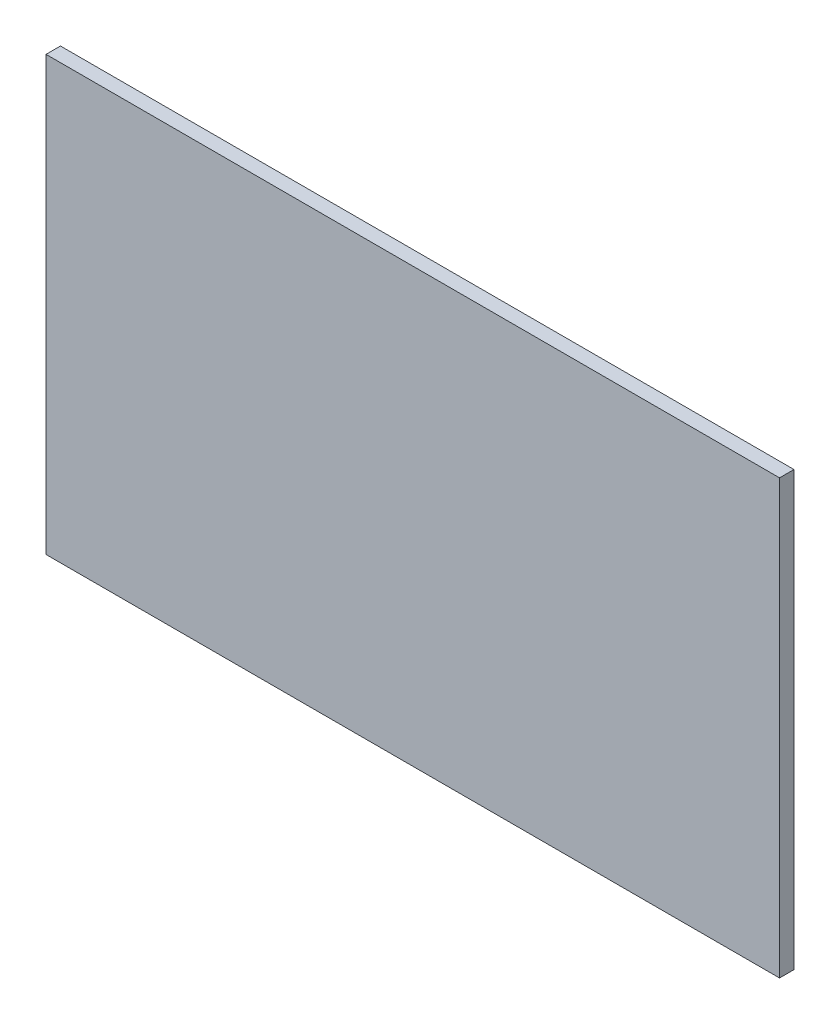
SolidWorks part; units mm, degrees
ref_plane "Front Plane" through (0, 0, 0) normal (0, 0, 1) x (1, 0, 0)
ref_plane "Top Plane" through (0, 0, 0) normal (0, 1, 0) x (1, 0, 0)
ref_plane "Right Plane" through (0, 0, 0) normal (1, 0, 0) x (0, 0, -1)
sketch "Sketch1" plane through (0, 0, 0) normal (0, 0, 1) x (1, 0, 0)
  line L1 (-25.4, -15) -> (25.4, -15)
  line L2 (-25.4, -15) -> (-25.4, 15)
  line L3 (-25.4, 15) -> (25.4, 15)
  line L4 (25.4, -15) -> (25.4, 15)
  line L5 (-25.4, -15) -> (25.4, 15) construction
  line L6 (-25.4, 15) -> (25.4, -15) construction
  point P0 (0, 0)
  dimension "D1" = 30
  dimension "D2" = 50.8
extrude "Boss-Extrude1" add sketch "Sketch1" along normal blind 1
sketch "Sketch2" [suppressed] plane through (0, 0, 0) normal (0, 0, 1) x (1, 0, 0)
  line L0 (-25.4, -15) -> (25.4, -15) construction
  line L1 (-7.4, 12) -> (7.6, 12)
  line L2 (-7.4, 12) -> (-7.4, 6)
  line L3 (-7.4, 6) -> (7.6, 6)
  line L4 (7.6, 12) -> (7.6, 6)
  line L5 (-7.4, 12) -> (7.6, 6) construction
  line L6 (-7.4, 6) -> (7.6, 12) construction
  line L7 (-25.4, 15) -> (-25.4, -15) construction
  line L8 (25.4, -15) -> (25.4, 15) construction
  line L10 (9.15, -1.1651) -> (14.65, -1.1651)
  line L11 (9.15, -1.1651) -> (9.15, -15)
  line L12 (9.15, -15) -> (14.65, -15)
  line L13 (14.65, -1.1651) -> (14.65, -15)
  line L14 (-5, 6) -> (5, 6)
  line L15 (-5, 6) -> (-5, -15)
  line L16 (-5, -15) -> (5, -15)
  line L17 (5, 6) -> (5, -15)
  circle A0 centre (11.9, 1) radius 3.5
  point P0 (0.1, 9)
  point P17 (0, -15)
  dimension "D6" = 7
  dimension "D1" = 27
  dimension "D2" = 6
  dimension "D3" = 15
  dimension "D4" = 33
  dimension "D5" = 16
  dimension "D7" = 13.5
  dimension "D8" = 5.5
  dimension "D9" = 10
extrude "Cut-Extrude2" [suppressed] cut sketch "Sketch2" against normal through all and the other way through all contours L4 L1 L2 L3 | L10 A0 | L17 L3 L15 L16 | L10 A0 | A0 L11 L12 L13
fillet "Fillet1" [suppressed] radius 1
equation "\"D1@Sketch2\"=20+7"
equation "\"D5@Sketch2\"=7.00+9"
